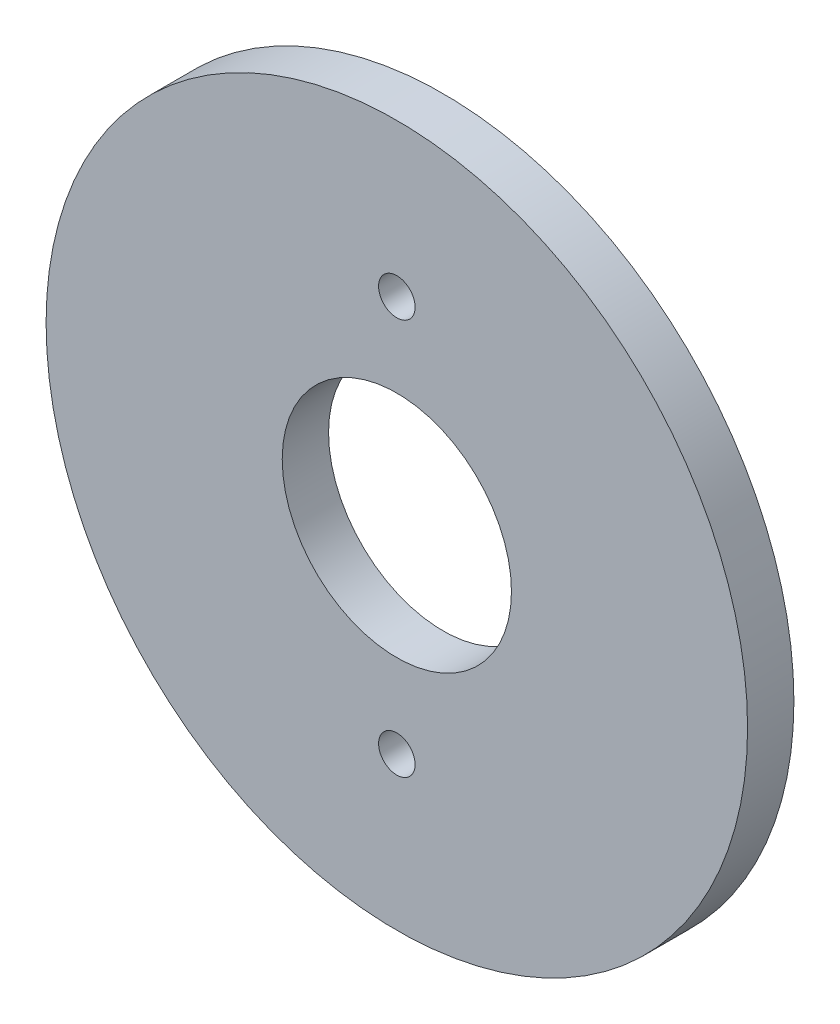
SolidWorks part; units mm, degrees
material "Cedar"
ref_plane "Front Plane" through (0, 0, 0) normal (0, 0, 1) x (1, 0, 0)
ref_plane "Top Plane" through (0, 0, 0) normal (0, 1, 0) x (1, 0, 0)
ref_plane "Right Plane" through (0, 0, 0) normal (1, 0, 0) x (0, 0, -1)
sketch "Sketch1" plane through (0, 0, 0) normal (0, 0, 1) x (1, 0, 0)
  circle A0 centre (0, 0) radius 33.655
  circle A1 centre (0, 18.9992) radius 1.7526
  circle A2 centre (0, 0) radius 10.9982
  circle A3 centre (0, -18.9992) radius 1.7526
  dimension "D1" = 67.31
  dimension "D2" = 3.5052
  dimension "D4" = 21.9964
  dimension "D5" = 3.5052
  dimension "D3" = 18.9992
  dimension "D6" = 18.9992
extrude "Boss-Extrude1" add sketch "Sketch1" along normal blind 4.445
